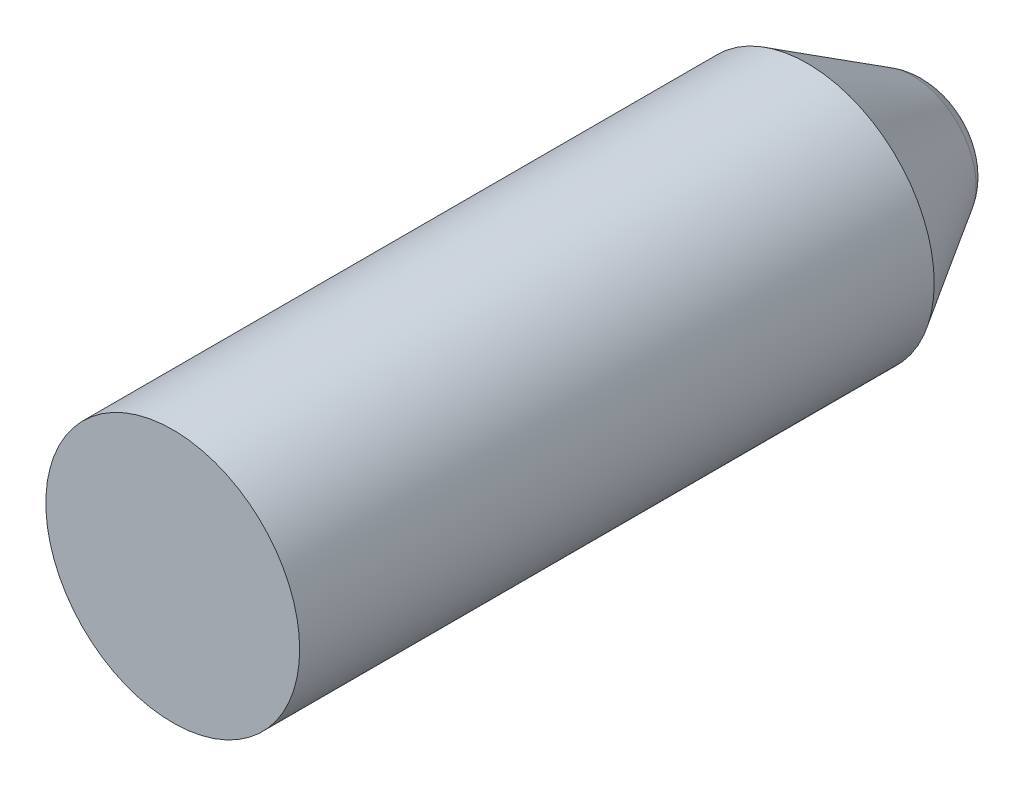
SolidWorks part; units mm, degrees
ref_plane "Front Plane" through (0, 0, 0) normal (0, 0, 1) x (1, 0, 0)
ref_plane "Top Plane" through (0, 0, 0) normal (0, 1, 0) x (1, 0, 0)
ref_plane "Right Plane" through (0, 0, 0) normal (1, 0, 0) x (0, 0, -1)
sketch "Sketch1" plane through (0, 0, 0) normal (0, 1, 0) x (1, 0, 0)
  line L0 (0, -998.9147) -> (0, 49001.0853) construction
  line L1 (0, 0) -> (5, 0)
  line L2 (5, 0) -> (5, 25)
  line L3 (5, 25) -> (2.5, 29.1522)
  line L4 (1, 30) -> (0, 30)
  line L5 (0, 0) -> (0, 30)
  arc A0 (2.5, 29.1522) -> (1, 30) centre (1, 28.2491) ccw
  point P9 (0, 0)
  point P11 (0, 0)
  point P12 (16.8227, 67.0194)
  point P13 (15.2495, 82.3523)
  point P14 (-4.9267, 47.095)
  point P15 (1.722, 45.8022)
  point P16 (5, 42.4778)
  point P17 (1.0517, 30)
  point P18 (5, 25.7646)
  point P19 (5, 24.437)
  point P20 (0, 0)
  dimension "D1" = 2.5
  dimension "D2" = 10
  dimension "D3" = 30
  dimension "D4" = 5
  dimension "D5" = 1
revolve "Revolve1" add sketch "Sketch1" angle 360 about L0
